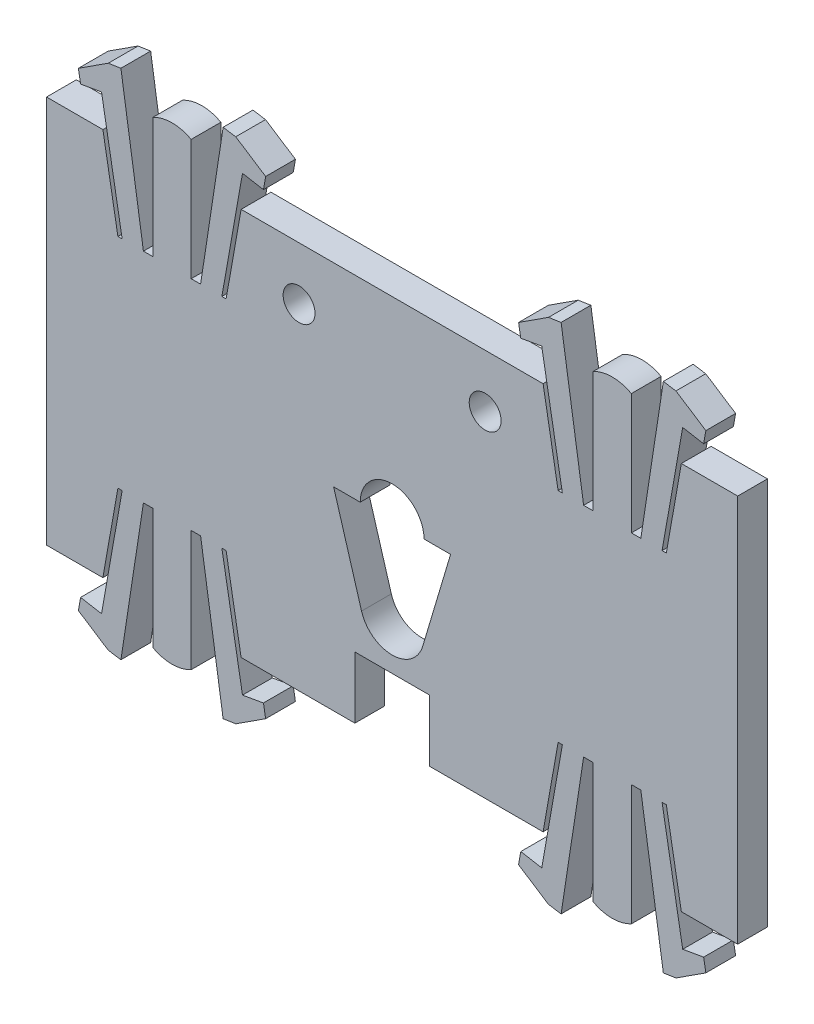
SolidWorks part; units mm, degrees
ref_plane "Přední rovina" through (0, 0, 0) normal (0, 0, 1) x (1, 0, 0)
ref_plane "Horní rovina" through (0, 0, 0) normal (0, 1, 0) x (1, 0, 0)
ref_plane "Pravá rovina" through (0, 0, 0) normal (1, 0, 0) x (0, 0, -1)
sketch "Model" plane through (0, 0, 0) normal (0, 0, 1) x (1, 0, 0)
  line L0 (-999.9987, 24.25) -> (49000.0013, 24.25) construction
  line L1 (-14.2, 18.25) -> (14.2, 18.25)
  line L2 (-27.2, -981.75) -> (-27.2, 49018.25) construction
  line L3 (-14.2, -981.75) -> (-14.2, 49018.25) construction
  line L4 (-20.7, -976.145) -> (-20.7, 49023.855) construction
  line L5 (32.5, 18.25) -> (27.2, 18.25)
  line L6 (25.7894, 10.25) -> (25.3894, 10.25)
  line L7 (25.7894, 10.25) -> (27.2, 18.25)
  line L8 (27.329, 21.25) -> (25.3894, 10.25)
  line L9 (29.2986, 20.9027) -> (27.329, 21.25)
  line L10 (29.2986, 20.9027) -> (29.507, 22.0845)
  line L11 (26.6932, 23.9074) -> (29.507, 22.0845)
  line L12 (25.507, 24.0889) -> (26.6932, 23.9074)
  line L13 (23.3894, 10.25) -> (25.507, 24.0889)
  line L19 (18.0106, 10.25) -> (15.893, 24.0889)
  line L20 (15.893, 24.0889) -> (14.7068, 23.9074)
  line L21 (14.7068, 23.9074) -> (11.893, 22.0845)
  line L25 (-1000, 10.25) -> (49000, 10.25) construction
  line L28 (-25.7894, 10.25) -> (-25.3894, 10.25)
  line L29 (-29.2986, 20.9027) -> (-29.507, 22.0845)
  line L30 (-25.507, 24.0889) -> (-26.6932, 23.9074)
  line L32 (-15.893, 24.0889) -> (-14.7068, 23.9074)
  line L33 (-14.7068, 23.9074) -> (-11.893, 22.0845)
  line L34 (-23.3894, 10.25) -> (-25.507, 24.0889)
  line L35 (-26.6932, 23.9074) -> (-29.507, 22.0845)
  line L36 (-29.2986, 20.9027) -> (-27.329, 21.25)
  line L37 (-27.329, 21.25) -> (-25.3894, 10.25)
  line L38 (-25.7894, 10.25) -> (-27.2, 18.25)
  line L39 (-27.2, 18.25) -> (-32.5, 18.25)
  line L40 (-12.1014, 20.9027) -> (-11.893, 22.0845)
  line L41 (-32.5, -18.25) -> (-32.5, 18.25)
  line L42 (32.5, -18.25) -> (32.5, 18.25)
  line L43 (-3.5, -12.45) -> (3.5, -12.45)
  line L44 (-27.2, -18.25) -> (-32.5, -18.25)
  line L45 (0, -7.95) -> (-2.875, -8.8069) construction
  line L46 (2.875, -8.8069) -> (5.5, 0)
  line L47 (5.5, 0) -> (3, 0)
  line L48 (-15.6106, -10.25) -> (-14.2, -18.25)
  line L49 (-15.6106, -10.25) -> (-16.0106, -10.25)
  line L50 (-14.071, -21.25) -> (-16.0106, -10.25)
  line L51 (-12.1014, -20.9027) -> (-14.071, -21.25)
  line L52 (-12.1014, -20.9027) -> (-11.893, -22.0845)
  line L53 (-14.7068, -23.9074) -> (-11.893, -22.0845)
  line L54 (-15.893, -24.0889) -> (-14.7068, -23.9074)
  line L56 (-18.0106, -10.25) -> (-15.893, -24.0889)
  line L58 (-14.2, -18.25) -> (-3.5, -18.25)
  line L59 (-3.5, -18.25) -> (-3.5, -12.45)
  line L63 (-23.3894, -10.25) -> (-25.507, -24.0889)
  line L64 (-25.507, -24.0889) -> (-26.6932, -23.9074)
  line L65 (-29.2986, -20.9027) -> (-29.507, -22.0845)
  line L66 (-26.6932, -23.9074) -> (-29.507, -22.0845)
  line L67 (-29.2986, -20.9027) -> (-27.329, -21.25)
  line L68 (-27.329, -21.25) -> (-25.3894, -10.25)
  line L69 (-25.7894, -10.25) -> (-27.2, -18.25)
  line L70 (-25.7894, -10.25) -> (-25.3894, -10.25)
  line L71 (27.2, -18.25) -> (32.5, -18.25)
  line L72 (25.7894, -10.25) -> (27.2, -18.25)
  line L73 (25.7894, -10.25) -> (25.3894, -10.25)
  line L74 (27.329, -21.25) -> (25.3894, -10.25)
  line L75 (29.2986, -20.9027) -> (27.329, -21.25)
  line L76 (29.2986, -20.9027) -> (29.507, -22.0845)
  line L77 (26.6932, -23.9074) -> (29.507, -22.0845)
  line L78 (25.507, -24.0889) -> (26.6932, -23.9074)
  line L79 (23.3894, -10.25) -> (25.507, -24.0889)
  line L81 (-2.875, -8.8069) -> (-5.5, 0)
  line L82 (-5.5, 0) -> (-3, 0)
  line L84 (0, -1000) -> (0, 49000) construction
  line L85 (-1000, 0) -> (49000, 0) construction
  line L86 (-12.1014, 20.9027) -> (-14.071, 21.25)
  line L87 (32.5, 18.25) -> (-32.5, 18.25) construction
  line L88 (32.5, 18.25) -> (32.5, -18.25) construction
  line L89 (32.5, -18.25) -> (-32.5, -18.25) construction
  line L90 (-32.5, 18.25) -> (-32.5, -18.25) construction
  line L91 (32.5, 18.25) -> (-32.5, -18.25) construction
  line L92 (32.5, -18.25) -> (-32.5, 18.25) construction
  line L95 (-18.0106, 10.25) -> (-15.893, 24.0889)
  line L96 (-14.071, 21.25) -> (-16.0106, 10.25)
  line L97 (-15.6106, 10.25) -> (-16.0106, 10.25)
  line L98 (-15.6106, 10.25) -> (-14.2, 18.25)
  line L99 (12.1014, 20.9027) -> (11.893, 22.0845)
  line L100 (12.1014, 20.9027) -> (14.071, 21.25)
  line L101 (14.071, 21.25) -> (16.0106, 10.25)
  line L102 (15.6106, 10.25) -> (16.0106, 10.25)
  line L103 (15.6106, 10.25) -> (14.2, 18.25)
  line L107 (18.0106, -10.25) -> (15.893, -24.0889)
  line L108 (15.893, -24.0889) -> (14.7068, -23.9074)
  line L109 (12.1014, -20.9027) -> (11.893, -22.0845)
  line L110 (14.7068, -23.9074) -> (11.893, -22.0845)
  line L111 (12.1014, -20.9027) -> (14.071, -21.25)
  line L112 (14.071, -21.25) -> (16.0106, -10.25)
  line L113 (15.6106, -10.25) -> (16.0106, -10.25)
  line L114 (15.6106, -10.25) -> (14.2, -18.25)
  line L115 (14.2, -18.25) -> (3.5, -18.25)
  line L116 (3.5, -18.25) -> (3.5, -12.45)
  line L121 (-22.5, 10.25) -> (-22.5, 21.5966)
  line L123 (-18.9, 10.25) -> (-18.9, 21.5966)
  line L128 (22.5, 10.25) -> (22.5, 21.5966)
  line L129 (18.9, 10.25) -> (18.9, 21.5966)
  line L132 (22.5, -10.25) -> (22.5, -21.5966)
  line L135 (18.9, -10.25) -> (18.9, -21.5966)
  line L138 (-18.9, -10.25) -> (-18.9, -21.5966)
  line L141 (-22.5, -10.25) -> (-22.5, -21.5966)
  line L142 (-22.5, 10.25) -> (-23.3894, 10.25)
  line L143 (-18.9, 10.25) -> (-18.0106, 10.25)
  line L144 (18.9, 10.25) -> (18.0106, 10.25)
  line L145 (22.5, 10.25) -> (23.3894, 10.25)
  line L146 (22.5, -10.25) -> (23.3894, -10.25)
  line L147 (18.9, -10.25) -> (18.0106, -10.25)
  line L148 (-18.9, -10.25) -> (-18.0106, -10.25)
  line L149 (-22.5, -10.25) -> (-23.3894, -10.25)
  line L150 (-10.6253, 11.75) -> (-7.157, 11.75) construction
  circle A0 centre (-8.75, 13.25) radius 1.5
  circle A1 centre (8.75, 13.25) radius 1.5
  circle A2 centre (0, -7.95) radius 3 construction
  circle A4 centre (0, 0) radius 3 construction
  arc A5 (-3, 0) -> (3, 0) centre (0, 0) cw
  arc A6 (-2.875, -8.8069) -> (2.875, -8.8069) centre (0, -7.95) ccw
  arc A7 (-24.5, 18.25) -> (-16.9, 18.25) centre (-20.7, 18.25) cw construction
  arc A12 (22.5, 21.5966) -> (18.9, 21.5966) centre (20.7, 18.25) ccw
  arc A15 (22.5, -21.5966) -> (18.9, -21.5966) centre (20.7, -18.25) cw
  arc A18 (-22.5, -21.5966) -> (-18.9, -21.5966) centre (-20.7, -18.25) ccw
  arc A19 (-22.5, 21.5966) -> (-18.9, 21.5966) centre (-20.7, 18.25) cw
  point P1 (0, 18.25)
  point P104 (0, -12.45)
  point P268 (0, 0)
  dimension "D17" = 30
  dimension "D19" = 3
  dimension "D22" = 4.5
  dimension "D23" = 6
  dimension "D24" = 6
  dimension "D26" = 1.8
  dimension "D14" = 3.8
  dimension "D27" = 5.5
  dimension "D1" = 65
  dimension "D2" = 36.5
  dimension "D3" = 6
  dimension "D4" = 13
  dimension "D5" = 14.2
  dimension "D6" = 0.4
  dimension "D7" = 8
  dimension "D8" = 2
  dimension "D9" = 80
  dimension "D10" = 2
  dimension "D11" = 3
  dimension "D12" = 2.6527
  dimension "D13" = 1.2
  dimension "D15" = 1.2
  dimension "D16" = 14
  dimension "D18" = 8.75
  dimension "D20" = 3.5
  dimension "D21" = 5.8
  dimension "D29" = 81.3
extrude "Přidat vysunutím1" add sketch "Model" along normal blind 2.8
